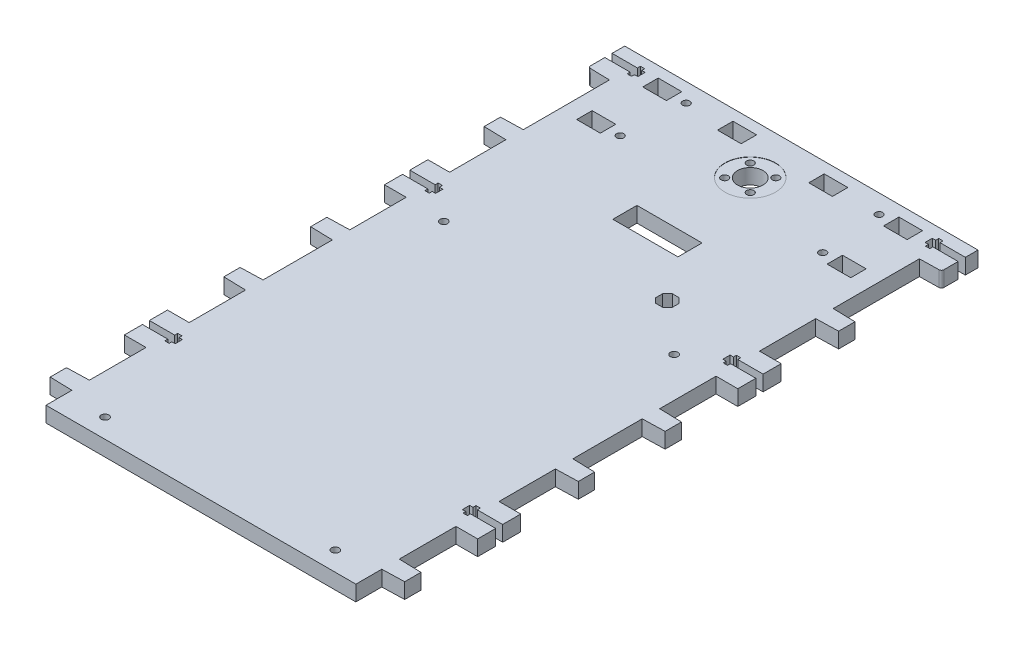
SolidWorks part; units mm, degrees
ref_plane "Front Plane" through (0, 0, 0) normal (0, 0, 1) x (1, 0, 0)
ref_plane "Top Plane" through (0, 0, 0) normal (0, 1, 0) x (1, 0, 0)
ref_plane "Right Plane" through (0, 0, 0) normal (1, 0, 0) x (0, 0, -1)
sketch "Sketch1" plane through (0, 0, 0) normal (0, 1, 0) x (1, 0, 0)
  line L0 (64.75, 251.99) -> (64.75, 3) construction
  line L1 (-8.5003, 251.99) -> (138.0003, 251.99)
  line L2 (93.179, 166.02) -> (95.2, 168.041)
  line L3 (0.5, 3) -> (129, 3)
  line L4 (17, 10.99) -> (112.5, 10.99) construction
  line L5 (2, 50.7445) -> (2, 51.9945)
  line L6 (129, 20.9943) -> (129, 44.4945)
  line L7 (138.0005, 159.8688) -> (127.5005, 159.8688)
  line L8 (88.3, 168.041) -> (90.321, 166.02)
  line L9 (83.6706, 247.44) -> (83.6706, 241.04) construction
  line L10 (129, 236.671) -> (129, 200.9501)
  line L11 (114.6706, 247.44) -> (114.6706, 241.04) construction
  line L12 (2, 56.1192) -> (3.8, 56.1192)
  line L13 (116.6706, 222.04) -> (116.6706, 215.64) construction
  line L14 (129, 20.9943) -> (129, 13.7443) construction
  line L15 (138.0003, 237.8405) -> (138.0003, 243.7503)
  line L16 (129, 17.3693) -> (138.25, 17.3693)
  line L17 (90.321, 172.92) -> (88.3, 170.899)
  line L18 (1.9997, 242.5003) -> (1.9997, 243.7503)
  line L19 (1.9997, 248) -> (3.7997, 248)
  line L20 (3.7997, 243.7503) -> (5.1997, 243.7503)
  line L21 (1.9997, 248) -> (1.9997, 246.75)
  line L22 (5.1997, 246.75) -> (5.1997, 243.7503)
  line L23 (3.7997, 242.5003) -> (3.7997, 243.7503)
  line L24 (3.7997, 246.75) -> (5.1997, 246.75)
  line L25 (1.9997, 242.5003) -> (3.7997, 242.5003)
  line L26 (3.7997, 248) -> (3.7997, 246.75)
  line L27 (-8.5003, 246.75) -> (1.9997, 246.75)
  line L28 (-8.5003, 243.7503) -> (1.9997, 243.7503)
  line L29 (128.9962, 92.9946) -> (128.9962, 85.7445) construction
  line L30 (129, 200.9501) -> (129, 193.7001) construction
  line L31 (93.179, 172.92) -> (90.321, 172.92)
  line L32 (128.9962, 92.9946) -> (138.25, 92.7446)
  line L33 (78.25, 197.31) -> (78.25, 187.31)
  line L34 (128.9962, 85.7445) -> (138.25, 85.9946)
  line L35 (138.25, 92.7446) -> (138.25, 85.9946)
  line L36 (3.8, 51.8695) -> (5.2, 51.8695)
  line L37 (0.5038, 128.9943) -> (0.5022, 121.7443) construction
  line L38 (128.9962, 128.9943) -> (138.25, 128.7443)
  line L39 (128.9978, 121.7443) -> (138.25, 121.9943)
  line L40 (129, 236.671) -> (137, 236.831)
  line L41 (0.5038, 92.9946) -> (0.5038, 85.7445) construction
  line L42 (0.5022, 121.7443) -> (0.5038, 92.9946)
  line L43 (-8.75, 128.7443) -> (-8.75, 121.9943)
  line L44 (0.5, 20.9943) -> (0.5, 44.4945)
  line L45 (129, 13.7443) -> (138.25, 13.9943)
  line L46 (128.9962, 85.7445) -> (128.9962, 62.3692)
  line L47 (138.25, 20.7443) -> (138.25, 13.9943)
  line L48 (129, 20.9943) -> (138.25, 20.7443)
  line L49 (0.5, 3) -> (0.5, 13.7443)
  line L50 (0.5, 20.9943) -> (0.5, 13.7443) construction
  line L51 (0.5, 20.9943) -> (-8.75, 20.7443)
  line L52 (138, 162.8686) -> (127.5, 162.8686)
  line L53 (125.7, 164.1186) -> (125.7, 162.8686)
  line L54 (138, 51.9945) -> (127.5, 51.9945)
  line L55 (138, 54.8692) -> (127.5, 54.8692)
  line L56 (125.7, 56.1192) -> (125.7, 54.8692)
  line L57 (78.25, 187.31) -> (51.25, 187.31)
  line L58 (-8.75, 20.7443) -> (-8.75, 13.9943)
  line L59 (0.5038, 152.3695) -> (0.5038, 128.9943)
  line L60 (127.5, 50.7445) -> (125.7, 50.7445)
  line L61 (111.7706, 215.64) -> (121.5706, 215.64)
  line L62 (111.7706, 222.04) -> (121.5706, 222.04)
  line L63 (0.5038, 85.7445) -> (0.5038, 62.3692)
  line L64 (0.5022, 121.7443) -> (-8.75, 121.9943)
  line L65 (111.7706, 222.04) -> (111.7706, 215.64)
  line L66 (121.5706, 222.04) -> (121.5706, 215.64)
  line L67 (0.5038, 128.9943) -> (-8.75, 128.7443)
  line L68 (-8.75, 92.7446) -> (-8.75, 85.9946)
  line L69 (127.5005, 158.6188) -> (125.7, 158.6188)
  line L70 (0.5038, 85.7445) -> (-8.75, 85.9946)
  line L71 (138.0003, 251.99) -> (138.0003, 246.75)
  line L72 (125.7, 54.8692) -> (124.3, 54.8692)
  line L73 (138, 44.4945) -> (129, 44.4945)
  line L74 (125.7, 50.7445) -> (125.7, 51.8695)
  line L75 (125.7, 162.8686) -> (124.3, 162.8686)
  line L76 (138, 54.8692) -> (138, 62.3692)
  line L77 (138, 152.3688) -> (128.9962, 152.3695)
  line L78 (2, 56.1192) -> (2, 54.8692)
  line L79 (5.2, 54.8692) -> (5.2, 51.8695)
  line L80 (-8.5, 51.9945) -> (-8.5, 44.4945)
  line L81 (-8.5, 62.3692) -> (0.5038, 62.3692)
  line L82 (-8.5, 54.8692) -> (-8.5, 62.3692)
  line L83 (3.8, 50.7445) -> (3.8, 51.8695)
  line L84 (-8.5, 44.4945) -> (0.5, 44.4945)
  line L85 (3.8, 54.8692) -> (5.2, 54.8692)
  line L86 (2, 50.7445) -> (3.8, 50.7445)
  line L87 (3.8, 56.1192) -> (3.8, 54.8692)
  line L88 (-8.5, 54.8692) -> (2, 54.8692)
  line L89 (-8.5, 51.9945) -> (2, 51.9945)
  line L90 (0.5038, 92.9946) -> (-8.75, 92.7446)
  line L91 (138, 62.3692) -> (128.9962, 62.3692)
  line L92 (125.7, 158.6188) -> (125.7, 159.8688)
  line L93 (0.5, 200.9501) -> (0.5, 193.7001) construction
  line L94 (138, 162.8686) -> (138, 170.3692)
  line L95 (138, 170.3692) -> (129, 170.3692)
  line L96 (138.0005, 159.8688) -> (138, 152.3688)
  line L97 (51.25, 197.31) -> (78.25, 197.31)
  line L98 (124.3, 162.8686) -> (124.3, 159.8688)
  line L99 (128.9962, 152.3695) -> (128.9962, 128.9943)
  line L100 (129, 193.7001) -> (129, 170.3692)
  line L101 (127.5, 164.1186) -> (127.5, 162.8686)
  line L102 (125.7, 159.8688) -> (124.3, 159.8688)
  line L103 (127.5, 164.1186) -> (125.7, 164.1186)
  line L104 (109.7706, 241.04) -> (119.5706, 241.04)
  line L105 (-8.75, 200.7001) -> (-8.75, 193.9501)
  line L106 (109.7706, 247.44) -> (119.5706, 247.44)
  line L107 (119.5706, 247.44) -> (119.5706, 241.04)
  line L108 (109.7706, 247.44) -> (109.7706, 241.04)
  line L109 (127.5005, 158.6188) -> (127.5005, 159.8688)
  line L110 (0.5, 193.7001) -> (-8.75, 193.9501)
  line L111 (138, 51.9945) -> (138, 44.4945)
  line L112 (124.3, 54.8692) -> (124.3, 51.8695)
  line L113 (0.5, 13.7443) -> (-8.75, 13.9943)
  line L114 (129, 3) -> (129, 13.7443)
  line L115 (127.5, 56.1192) -> (127.5, 54.8692)
  line L116 (125.7, 51.8695) -> (124.3, 51.8695)
  line L117 (127.5, 56.1192) -> (125.7, 56.1192)
  line L118 (0.5, 200.9501) -> (-8.75, 200.7001)
  line L119 (12.8294, 222.04) -> (12.8294, 215.64) construction
  line L120 (14.8294, 247.44) -> (14.8294, 241.04) construction
  line L121 (45.8294, 247.44) -> (45.8294, 241.04) construction
  line L122 (50.7294, 247.44) -> (50.7294, 241.04)
  line L123 (40.9294, 247.44) -> (40.9294, 241.04)
  line L124 (50.7294, 241.04) -> (40.9294, 241.04)
  line L125 (50.7294, 247.44) -> (40.9294, 247.44)
  line L126 (138.25, 128.7443) -> (138.25, 121.9943)
  line L127 (128.9978, 121.7443) -> (128.9962, 92.9946)
  line L128 (0.5, 17.3693) -> (-8.75, 17.3693)
  line L129 (127.5, 50.7445) -> (127.5, 51.9945)
  line L130 (0.5, 193.7001) -> (0.5, 170.3692)
  line L131 (1.9995, 158.6188) -> (1.9995, 159.8688)
  line L132 (2, 164.1186) -> (3.8, 164.1186)
  line L133 (3.8, 159.8688) -> (5.2, 159.8688)
  line L134 (2, 164.1186) -> (2, 162.8686)
  line L135 (129, 200.9501) -> (138.25, 200.7001)
  line L136 (19.7294, 247.44) -> (19.7294, 241.04)
  line L137 (9.9294, 247.44) -> (9.9294, 241.04)
  line L138 (19.7294, 247.44) -> (9.9294, 247.44)
  line L139 (19.7294, 241.04) -> (9.9294, 241.04)
  line L140 (129, 193.7001) -> (138.25, 193.9501)
  line L141 (138.25, 200.7001) -> (138.25, 193.9501)
  line L142 (5.2, 162.8686) -> (5.2, 159.8688)
  line L143 (78.7706, 247.44) -> (88.5706, 247.44)
  line L144 (78.7706, 241.04) -> (88.5706, 241.04)
  line L145 (88.5706, 247.44) -> (88.5706, 241.04)
  line L146 (78.7706, 247.44) -> (78.7706, 241.04)
  line L147 (-8.5005, 159.8688) -> (-8.5, 152.3688)
  line L148 (-8.5, 170.3692) -> (0.5, 170.3692)
  line L149 (-8.5, 162.8686) -> (-8.5, 170.3692)
  line L150 (3.8, 158.6188) -> (3.8, 159.8688)
  line L151 (-8.5, 152.3688) -> (0.5038, 152.3695)
  line L152 (3.8, 162.8686) -> (5.2, 162.8686)
  line L153 (1.9995, 158.6188) -> (3.8, 158.6188)
  line L154 (3.8, 164.1186) -> (3.8, 162.8686)
  line L155 (-8.5, 162.8686) -> (2, 162.8686)
  line L156 (-8.5005, 159.8688) -> (1.9995, 159.8688)
  line L157 (90.321, 166.02) -> (93.179, 166.02)
  line L158 (138.0003, 243.7503) -> (127.5003, 243.7503)
  line L159 (138.0003, 246.75) -> (127.5003, 246.75)
  line L160 (125.7003, 248) -> (125.7003, 246.75)
  line L161 (127.5003, 242.5003) -> (125.7003, 242.5003)
  line L162 (125.7003, 246.75) -> (124.3003, 246.75)
  line L163 (125.7003, 242.5003) -> (125.7003, 243.7503)
  line L164 (124.3003, 246.75) -> (124.3003, 243.7503)
  line L165 (127.5003, 248) -> (127.5003, 246.75)
  line L166 (125.7003, 243.7503) -> (124.3003, 243.7503)
  line L167 (127.5003, 248) -> (125.7003, 248)
  line L168 (127.5003, 242.5003) -> (127.5003, 243.7503)
  line L169 (0.5, 236.671) -> (0.5, 200.9501)
  line L170 (-8.5003, 251.99) -> (-8.5003, 246.75)
  line L171 (88.3, 170.899) -> (88.3, 168.041)
  line L172 (95.2, 170.899) -> (93.179, 172.92)
  line L173 (7.9294, 222.04) -> (7.9294, 215.64)
  line L174 (17.7294, 222.04) -> (17.7294, 215.64)
  line L175 (17.7294, 222.04) -> (7.9294, 222.04)
  line L176 (17.7294, 215.64) -> (7.9294, 215.64)
  line L177 (95.2, 168.041) -> (95.2, 170.899)
  line L178 (90.321, 172.92) -> (93.179, 166.02) construction
  line L179 (93.179, 172.92) -> (90.321, 166.02) construction
  line L180 (95.2, 168.041) -> (88.3, 170.899) construction
  line L181 (95.2, 170.899) -> (88.3, 168.041) construction
  line L182 (64.75, 151.47) -> (64.75, 169.47) construction
  line L183 (64.75, 169.47) -> (91.75, 169.47) construction
  line L184 (91.75, 172.92) -> (91.75, 166.02) construction
  line L188 (0.5, 236.671) -> (-7.5, 236.831)
  line L192 (51.25, 197.31) -> (51.25, 187.31)
  line L205 (-8.5003, 237.8405) -> (-8.5003, 243.7503)
  line L209 (0.5, 230.79) -> (129, 230.79) construction
  line L212 (17, 151.47) -> (112.5, 151.47) construction
  circle A0 centre (112.5, 10.99) radius 1.575
  arc A1 (-7.5, 236.831) -> (-8.5003, 237.8405) centre (-7.4908, 237.8405) cw
  circle A2 centre (22.7544, 218.84) radius 1.5
  circle A3 centre (112.5, 151.47) radius 1.575
  circle A4 centre (64.75, 230.79) radius 5.25
  circle A5 centre (24.7544, 244.24) radius 1.5
  circle A6 centre (70.0533, 236.0933) radius 1.5
  circle A7 centre (70.0533, 225.4867) radius 1.5
  circle A9 centre (104.7456, 244.24) radius 1.5
  circle A10 centre (106.7456, 218.84) radius 1.5
  circle A11 centre (59.4467, 225.4867) radius 1.5
  circle A12 centre (59.4467, 236.0933) radius 1.5
  circle A13 centre (17, 151.47) radius 1.575
  arc A14 (137, 236.831) -> (138.0003, 237.8405) centre (136.9908, 237.8405) ccw
  circle A15 centre (17, 10.99) radius 1.575
  circle A16 centre (70.4069, 236.4469) radius 1.5 construction
  circle A17 centre (59.0931, 236.4469) radius 1.5 construction
  circle A18 centre (70.4069, 225.1331) radius 1.5 construction
  circle A19 centre (59.0931, 225.1331) radius 1.5 construction
  point P6 (64.75, 151.47)
  point P159 (64.75, 10.99)
  point P188 (64.75, 197.31)
  point P228 (64.75, 187.31)
  dimension "D4" = 6.9
  dimension "D3" = 27
  dimension "D2" = 18
extrude "Boss-Extrude1" add sketch "Sketch1" along normal blind 6.4
sketch "Sketch2" plane through (0, 6.4, 0) normal (0, 1, 0) x (1, 0, 0)
  circle A0 centre (64.75, 230.79) radius 10.5
  dimension "D1" = 21
extrude "Cut-Extrude1" cut sketch "Sketch2" against normal blind 0.1
